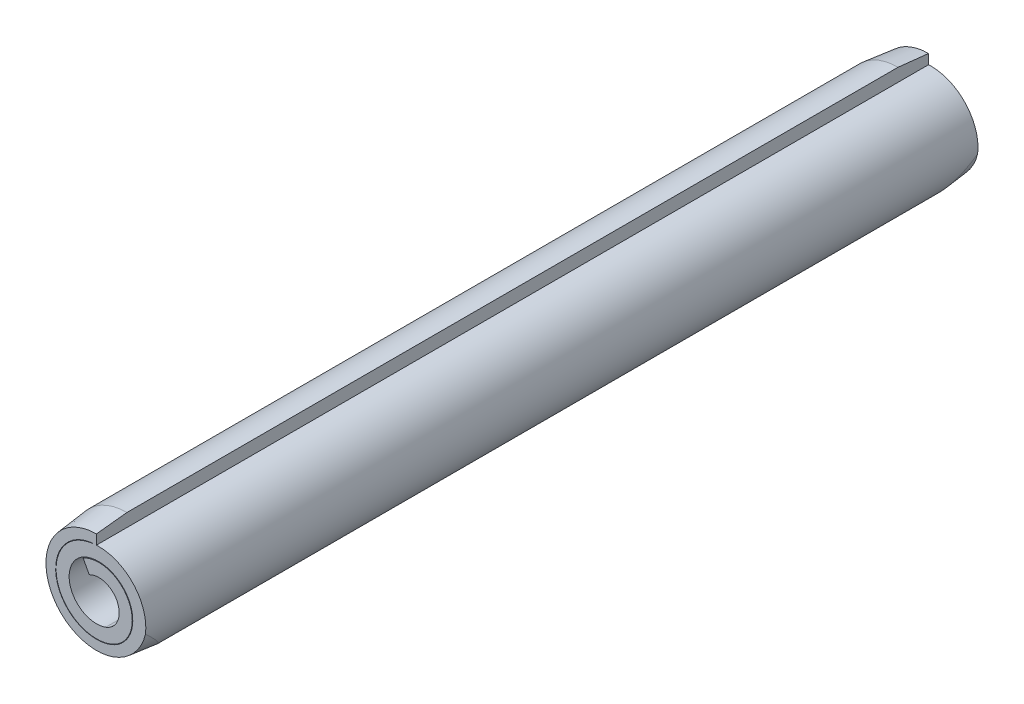
SolidWorks part; units mm, degrees
material "Alloy Steel"
ref_plane "Front Plane" through (0, 0, 0) normal (0, 0, 1) x (1, 0, 0)
ref_plane "Top Plane" through (0, 0, 0) normal (0, 1, 0) x (1, 0, 0)
ref_plane "Right Plane" through (0, 0, 0) normal (1, 0, 0) x (0, 0, -1)
sketch "Sketch1" plane through (0, 0, 0) normal (0, 0, 1) x (1, 0, 0)
  line L0 (0, 0) -> (0, 2.4638) construction
  line L1 (0, 0.6159) -> (0, 1.2319) construction
  line L2 (0, 1.2319) -> (0, 1.8478) construction
  line L3 (0, 0.6159) -> (0, 0) construction
  line L4 (0, -0.6159) -> (0, 0) construction
  line L5 (0, -0.6159) -> (0, -1.2319) construction
  line L6 (0, -1.2319) -> (0, -1.8478) construction
  line L7 (0, 0) -> (-0.8427, 2.3152) construction
  line L8 (0, 0) -> (0.8427, -2.3152) construction
  circle A0 centre (0, 0) radius 2.4638
  point P0 (0, -0.6159)
  point P3 (0, 0.6159)
  point P5 (0, 1.2319)
  point P6 (0, 1.8478)
  point P9 (0, -1.2319)
  point P12 (0, -1.8478)
  dimension "OD" = 4.9276
  dimension "D2" = 2.4638
  dimension "D3" = 0.6159
  dimension "D4" = 20
  dimension "D5" = 20
sketch "Sketch2" plane through (0, 0, 0) normal (0, 0, 1) x (1, 0, 0)
  line L0 (0, 0) -> (-0.8427, 2.3152) construction
  line L1 (0, 0) -> (0, 2.4638) construction
  line L2 (0, 0) -> (0.8427, -2.3152) construction
  line L3 (0, 0) -> (-1.2319, 2.1337) construction
  arc A0 (0, 2.4638) -> (0.8427, -2.3152) centre (0, 0) ccw
  arc A2 (0.8427, -2.3152) -> (-0.632, 1.7364) centre (0.1053, -0.2894) ccw
  arc A3 (-0.632, 1.7364) -> (0.632, -1.7364) centre (0, 0) ccw
  arc A4 (0.632, -1.7364) -> (-0.6102, 1.057) centre (0.1079, -0.2966) ccw
  circle A5 centre (0, 0) radius 2.4638 construction
  dimension "D1" = 20
  dimension "D2" = 10
extrude "Extrude-Thin1" add sketch "Sketch2" against normal mid plane 38.1 thin thin type one direction reverse wall 0.5975
sketch "Sketch3" plane through (0, 0, 0) normal (1, 0, 0) x (0, 0, -1)
  line L0 (-19.05, 2.4638) -> (-19.05, 2.3114)
  line L1 (-19.05, 2.3114) -> (-17.653, 2.4638)
  line L2 (-17.653, 2.4638) -> (-19.05, 2.4638)
  line L3 (0, 0) -> (-19.05, 0) construction
  line L4 (-19.05, 1.8664) -> (-19.05, -2.3152) construction
  line L5 (-17.653, -2.4638) -> (-19.05, -2.4638) construction
  line L6 (-19.05, -2.3114) -> (-17.653, -2.4638) construction
  line L7 (-19.05, -2.4638) -> (-19.05, -2.3114) construction
  line L8 (0, 0) -> (0, 2.4638) construction
  line L9 (19.05, 2.4638) -> (-19.05, 2.4638) construction
  line L10 (17.653, 2.4638) -> (19.05, 2.4638)
  line L11 (19.05, 2.3114) -> (17.653, 2.4638)
  line L12 (19.05, 2.4638) -> (19.05, 2.3114)
  dimension "Chamfer Lenght" = 1.397
  dimension "B" = 4.6228
revolve "Cut-Revolve1" cut sketch "Sketch3" angle 360 about L3
equation "\"D3@Sketch1\" = \"D2@Sketch1\"/4"
equation "\"D5@Extrude-Thin1\" = \"D3@Sketch1\"*.97"
